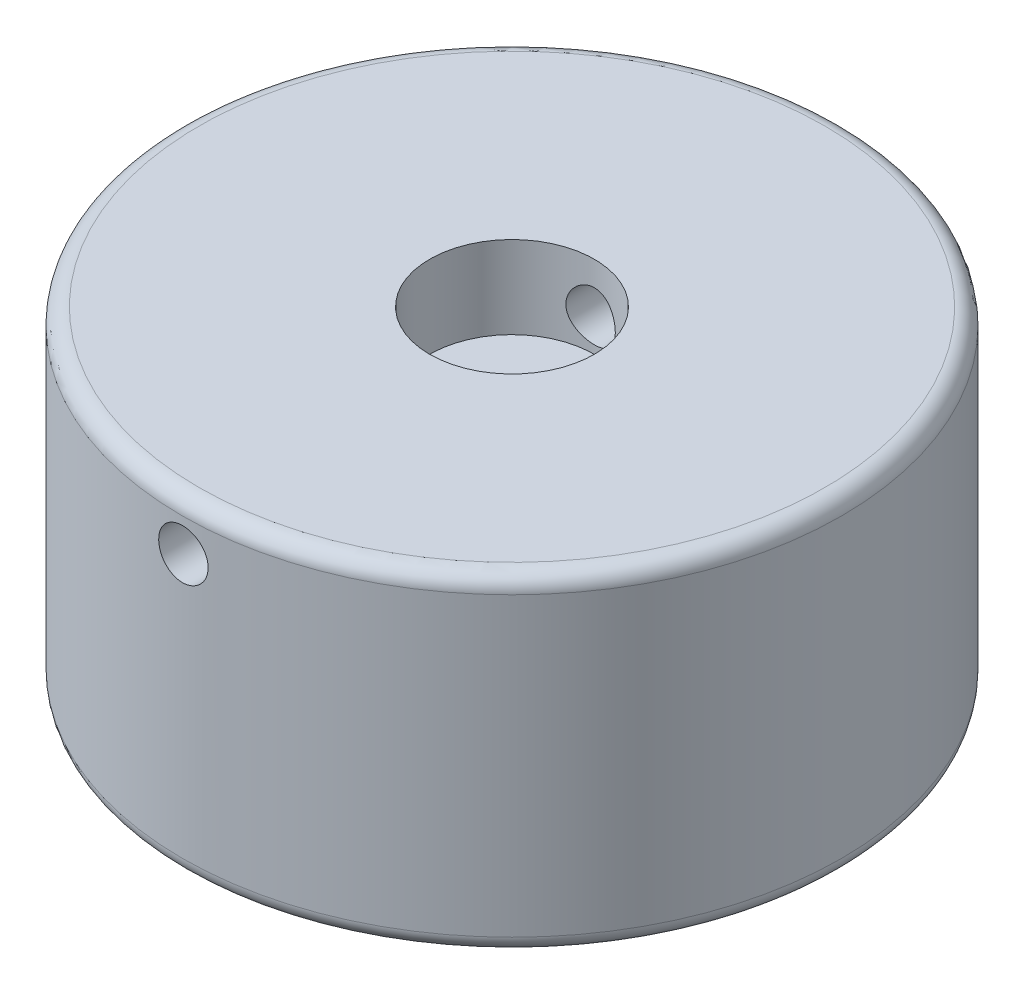
SolidWorks part; units mm, degrees
ref_plane "Front Plane" through (0, 0, 0) normal (0, 0, 1) x (1, 0, 0)
ref_plane "Top Plane" through (0, 0, 0) normal (0, 1, 0) x (1, 0, 0)
ref_plane "Right Plane" through (0, 0, 0) normal (1, 0, 0) x (0, 0, -1)
sketch "Sketch1" plane through (0, 0, 0) normal (0, 1, 0) x (1, 0, 0)
  circle A0 centre (0, 0) radius 20
extrude "Boss-Extrude1" add sketch "Sketch1" along normal blind 20
sketch "Sketch2" plane through (0, 20, 0) normal (0, 1, 0) x (1, 0, 0)
  circle A0 centre (0, 0) radius 5
extrude "Cut-Extrude1" cut sketch "Sketch2" against normal blind 5
ref_plane "Plane1" through (0, 0, 20) normal (0, 0, 1) x (1, 0, 0)
sketch "Sketch3" plane through (0, 0, 20) normal (0, 0, 1) x (1, 0, 0)
  line L0 (0, 20.7696) -> (0, 17) construction
  line L1 (20, 20) -> (-20, 20) construction
  circle A0 centre (0, 17) radius 1.5
  dimension "D1" = 3
extrude "Cut-Extrude2" cut sketch "Sketch3" against normal through all
fillet "Fillet1" radius 1 1 edges at (0, 0, 20)
fillet "Fillet2" radius 1 1 edges at (0, 20, 20)
